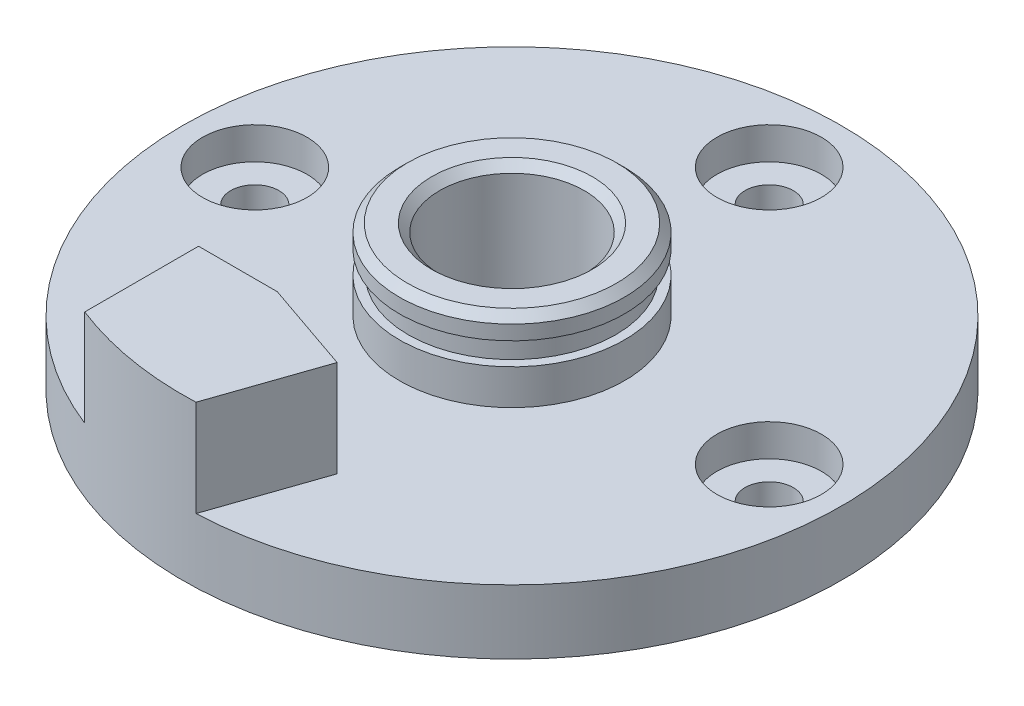
SolidWorks part; units mm, degrees
ref_plane "前视基准面" through (0, 0, 0) normal (0, 0, 1) x (1, 0, 0)
ref_plane "上视基准面" through (0, 0, 0) normal (0, 1, 0) x (1, 0, 0)
ref_plane "右视基准面" through (0, 0, 0) normal (1, 0, 0) x (0, 0, -1)
sketch "草图1" plane through (0, 0, 0) normal (0, 0, 1) x (1, 0, 0)
  line L18 (-4.5, 0) -> (-20.5, 0)
  line L19 (-20.5, 0) -> (-20.5, 4)
  line L20 (-20.5, 4) -> (-7, 4)
  line L21 (-7, 4) -> (-7, 6.2)
  line L22 (-7, 9) -> (-4.5, 9)
  line L23 (0, 7) -> (0, 0) construction
  line L24 (-4.5, 0) -> (-4.5, 9)
  line L25 (-7, 6.2) -> (-6.45, 6.2)
  line L26 (-6.45, 6.2) -> (-6.45, 7.6)
  line L27 (-6.45, 7.6) -> (-7, 7.6)
  line L28 (-7, 7.6) -> (-7, 9)
  point P0 (0, 0)
  point P6 (0, 0)
  point P11 (0, 0)
  dimension "D1" = 2.5
  dimension "D2" = 1.4
  dimension "D3" = 4.5
  dimension "D4" = 16
  dimension "D5" = 0.55
  dimension "D6" = 2.2
  dimension "D7" = 4
  dimension "D9" = 5
revolve "旋转1" add sketch "草图1" angle 360 about L23
sketch "草图2" plane through (0, 0, 0) normal (0, 1, 0) x (1, 0, 0)
  line L0 (0, 16) -> (0, -16) construction
  line L1 (-16, 0) -> (16, 0) construction
  circle A0 centre (0, 0) radius 16 construction
  circle A1 centre (-16, 0) radius 1.5
  circle A2 centre (0, 16) radius 1.5
  circle A4 centre (16, 0) radius 1.5
  dimension "D1" = 32
extrude "切除-拉伸1" cut sketch "草图2" along normal through all
sketch "草图3" plane through (0, 0, 0) normal (0, 1, 0) x (1, 0, 0)
  circle A0 centre (-16, 0) radius 3.25
  circle A2 centre (0, 16) radius 3.25
  circle A3 centre (16, 0) radius 3.25
  dimension "D1" = 6.5
  dimension "D2" = 6.5
  dimension "D3" = 6.5
extrude "切除-拉伸2" cut sketch "草图3" against normal blind 2 from surface at 4 starting at face at (-17.5, 4, 0)
sketch "草图4" plane through (0, 4, 0) normal (0, 1, 0) x (1, 0, 0)
  line L1 (7.5, -12) -> (-7.5, -12)
  line L2 (7.5, -12) -> (7.5, -19.0788)
  line L4 (-7.5, -12) -> (-7.5, -19.0788)
  circle A0 centre (0, 0) radius 20.5 construction
  arc A2 (7.5, -19.0788) -> (-7.5, -19.0788) centre (0, 0) cw
  circle A4 centre (0, 0) radius 4.5 construction
  dimension "D3" = 7.5
  dimension "D1" = 15
  dimension "D2" = 12
extrude "凸台-拉伸1" add sketch "草图4" along normal blind 6
sketch "草图5" plane through (0, 0, 0) normal (0, -1, 0) x (1, 0, 0)
  circle A0 centre (0, 0) radius 7.5
  dimension "15" = 15
extrude "切除-拉伸3" cut sketch "草图5" against normal blind 1
chamfer "倒角1" distance 0.5 angle 45 2 edges at (-4.5, 9, 0) (4.5, 1, 0)
chamfer "倒角2" distance 0.5 angle 45 1 edges at (-7, 9, 0)
sketch "草图6" plane through (0, 10, 0) normal (0, 1, 0) x (1, 0, 0)
  line L1 (1.9677, -14.0337) -> (-1.3537, -21.4937)
  line L2 (1.9677, -14.0337) -> (-2.6, -12)
  line L3 (7.5, -12) -> (-7.5, -12) construction
  line L4 (-2.6, -12) -> (7.5, -12)
  line L5 (7.5, -12) -> (7.5, -20.9089)
  line L6 (-1.3537, -21.4937) -> (7.5, -20.9089)
  line L7 (-7.5, -12) -> (-7.5, -19.0788) construction
  dimension "D1" = 24
  dimension "D2" = 5
  dimension "D3" = 4.9
  dimension "D4" = 90
extrude "切除-拉伸4" cut sketch "草图6" against normal blind 6
sketch "草图7" plane through (0, 4, 0) normal (0, 1, 0) x (1, 0, 0)
  line L0 (-2.6, -12) -> (3.0731, -13.9534)
  line L1 (3.0731, -13.9534) -> (0.8247, -20.4834)
  line L2 (-2.6, -12) -> (1.9677, -14.0337)
  line L3 (1.9677, -14.0337) -> (-0.9024, -20.4801)
  arc A0 (-0.9024, -20.4801) -> (0.8247, -20.4834) centre (0, 0) ccw
  dimension "D1" = 5
  dimension "D2" = 6
extrude "凸台-拉伸2" add sketch "草图7" along normal blind 6
